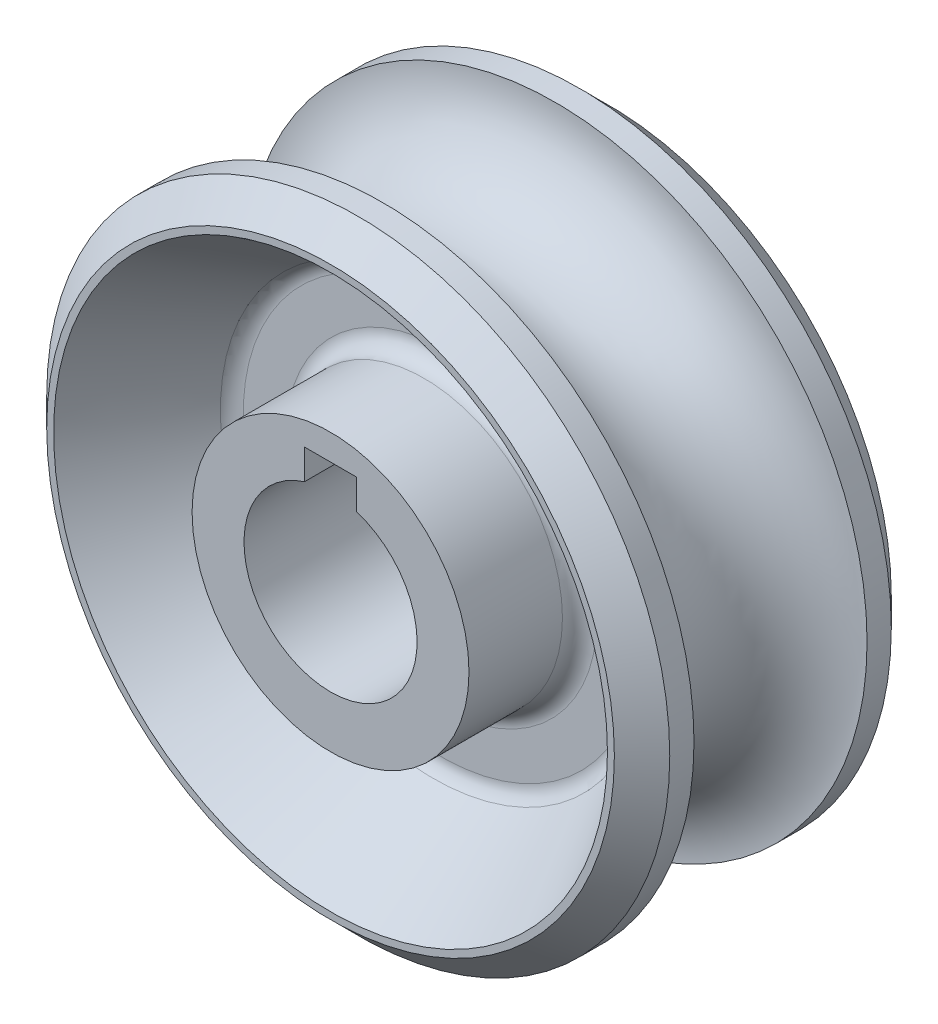
SolidWorks part; units mm, degrees
material "AISI 1020"
ref_plane "Front Plane" through (0, 0, 0) normal (0, 0, 1) x (1, 0, 0)
ref_plane "Top Plane" through (0, 0, 0) normal (0, 1, 0) x (1, 0, 0)
ref_plane "Right Plane" through (0, 0, 0) normal (1, 0, 0) x (0, 0, -1)
sketch "Base Sketch" plane through (0, 0, 0) normal (0, 0, 1) x (1, 0, 0)
  circle A0 centre (0, 0) radius 28.575
  circle A1 centre (0, 0) radius 7.9375
  dimension "D1" = 57.15
  dimension "D2" = 15.875
extrude "Base" add sketch "Base Sketch" along normal mid plane 25.4
sketch "Groove Sketch" plane through (0, 0, 0) normal (1, 0, 0) x (0, 0, -1)
  line L0 (12.7, 28.575) -> (-12.7, 28.575) construction
  line L1 (0, 0) -> (25.0554, 0) construction
  circle A0 centre (0, 28.575) radius 7.9375
  dimension "D1" = 15.875
revolve "Outer Revolved Cut" cut sketch "Groove Sketch" angle 360 about L1
sketch "Sketch3" plane through (0, 0, 0) normal (1, 0, 0) x (0, 0, -1)
  line L0 (12.7, 12.7) -> (2.54, 12.7)
  line L1 (12.7, -28.575) -> (12.7, 28.575) construction
  line L2 (2.54, 12.7) -> (2.54, 19.05)
  line L3 (2.54, 19.05) -> (12.7, 25.4)
  line L4 (12.7, 25.4) -> (12.7, 12.7)
  line L5 (0, 0) -> (27.599, 0) construction
  line L6 (0, 0) -> (0, 38.1046) construction
  line L7 (-12.7, 25.4) -> (-12.7, 12.7)
  line L8 (-12.7, 12.7) -> (-2.54, 12.7)
  line L9 (-2.54, 12.7) -> (-2.54, 19.05)
  line L10 (-2.54, 19.05) -> (-12.7, 25.4)
  dimension "D1" = 6.35
  dimension "D2" = 10.16
  dimension "D3" = 50.8
  dimension "D4" = 25.4
revolve "Inner Revolved Cut" cut sketch "Sketch3" angle 360 about L5
chamfer "Outer Chamfer" distance 2.54 angle 45 2 edges at (28.575, 0, -12.7) (28.575, 0, 12.7)
fillet "Inner Fillet" radius 1.5875 4 edges at (19.05, 0, -2.54) (12.7, 0, -2.54) (12.7, 0, 2.54) (19.05, 0, 2.54)
sketch "Keyway Sketch" plane through (0, 0, 0) normal (0, 0, 1) x (1, 0, 0)
  line L1 (2.3876, 0) -> (-2.3876, 0)
  line L2 (2.3876, 0) -> (2.3876, 10.3251)
  line L3 (2.3876, 10.3251) -> (-2.3876, 10.3251)
  line L4 (-2.3876, 0) -> (-2.3876, 10.3251)
  line L5 (2.3876, 0) -> (-2.3876, 10.3251) construction
  line L6 (2.3876, 10.3251) -> (-2.3876, 0) construction
  circle A1 centre (0, 0) radius 7.9375 construction
  point P0 (0, 5.1626)
  dimension "D1" = 4.7752
  dimension "D2" = 2.3876
extrude "Keyway" cut sketch "Keyway Sketch" against normal through all and the other way through all
